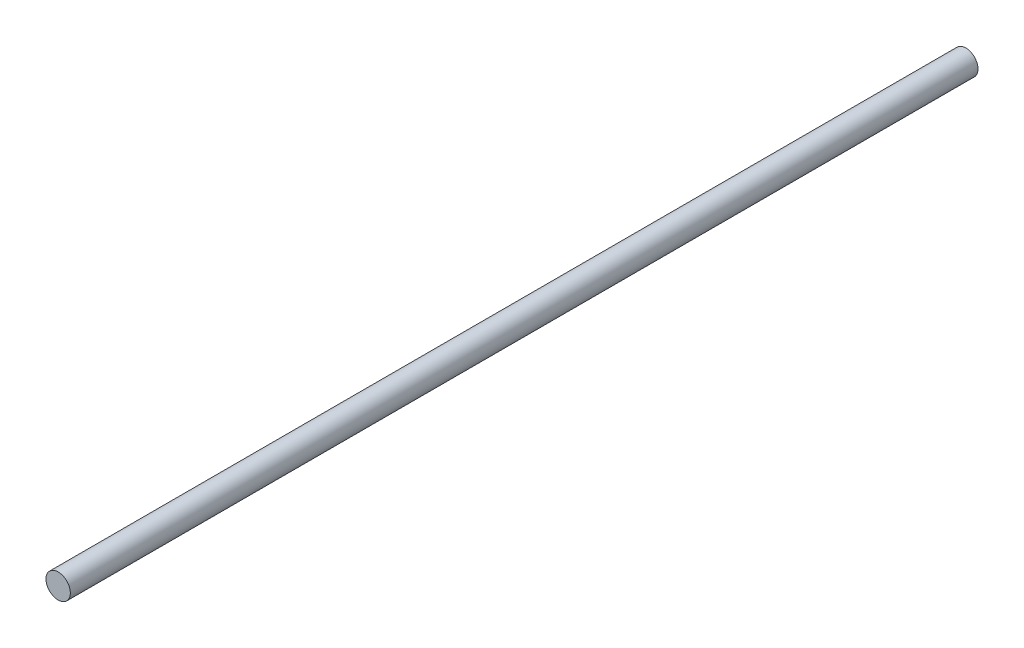
SolidWorks part; units mm, degrees
ref_plane "Front Plane" through (0, 0, 0) normal (0, 0, 1) x (1, 0, 0)
ref_plane "Top Plane" through (0, 0, 0) normal (0, 1, 0) x (1, 0, 0)
ref_plane "Right Plane" through (0, 0, 0) normal (1, 0, 0) x (0, 0, -1)
sketch "base" plane through (0, 0, 0) normal (0, 0, 1) x (1, 0, 0)
  circle A0 centre (0, 0) radius 51
  arc A1 (10.1018, 49.9895) -> (-10.1018, 49.9895) centre (0, 0) ccw construction
extrude "Boss-Extrude1" add sketch "base" along normal blind 2800 and the other way blind 1000
sketch "center" plane through (0, 0, 0) normal (0, 1, 0) x (1, 0, 0)
  line L0 (0, -2800) -> (0, 1000) construction
  line L1 (-51, -2800) -> (51, -2800) construction
  line L2 (51, 1000) -> (-51, 1000) construction
sketch "cutout" plane through (0, 0, 0) normal (0, 0, 1) x (1, 0, 0)
  circle A0 centre (0, 0) radius 49.5
  circle A1 centre (0, 0) radius 51 construction
  dimension "D1" = 1.5
extrude "Cut-Extrude1" cut sketch "cutout" against normal offset from surface 10 and the other way offset from surface (2790 mm away) 10 up to face at (51, 0, -1000) other way up to face at (51, 0, 2800)
